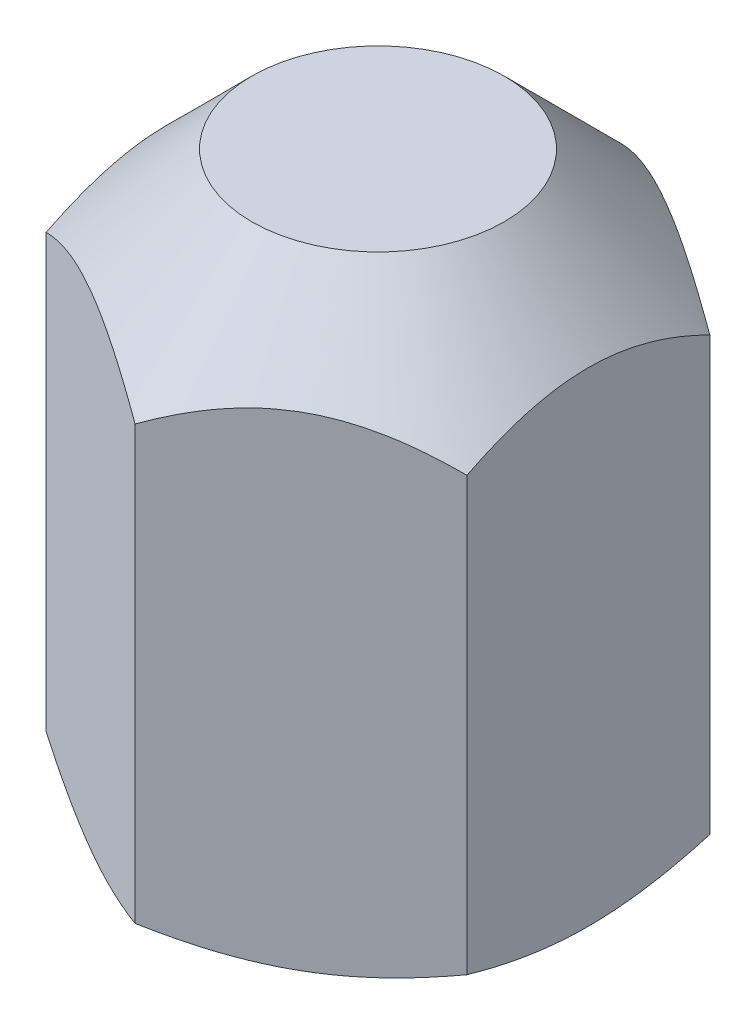
SolidWorks part; units mm, degrees
ref_plane "Přední rovina" through (0, 0, 0) normal (0, 0, 1) x (1, 0, 0)
ref_plane "Vrchní rovina" through (0, 0, 0) normal (0, 1, 0) x (1, 0, 0)
ref_plane "Pravá rovina" through (0, 0, 0) normal (1, 0, 0) x (0, 0, -1)
sketch "Skica1" plane through (0, 0, 0) normal (0, 1, 0) x (1, 0, 0)
  line L1 (5, -2.8868) -> (5, 2.8868)
  line L2 (5, 2.8868) -> (0, 5.7735)
  line L3 (0, 5.7735) -> (-5, 2.8868)
  line L4 (-5, 2.8868) -> (-5, -2.8868)
  line L5 (-5, -2.8868) -> (0, -5.7735)
  line L6 (0, -5.7735) -> (5, -2.8868)
  circle A0 centre (0, 0) radius 5 construction
  dimension "s" = 10
extrude "Vysunout1" add sketch "Skica1" along normal blind 13.5
sketch "Skica2" plane through (0, 0, 0) normal (1, 0, 0) x (0, 0, -1)
  line L0 (0, 13.5) -> (0, 0) construction
  line L1 (-2.8868, 13.5) -> (2.8868, 13.5) construction
  line L2 (-5.7735, 13.5) -> (-5.7735, 10.7265)
  line L3 (-5.7735, 13.5) -> (-5.7735, 0) construction
  line L4 (-5.7735, 10.7265) -> (-3, 13.5)
  line L5 (-3, 13.5) -> (-5.7735, 13.5)
  dimension "D1" = 45
  dimension "k" = 6
revolve "Odebrat otočením1" cut sketch "Skica2" angle 360 about L0
sketch "Skica3" plane through (0, 0, 0) normal (0, 0, 1) x (1, 0, 0)
  line L0 (5, 0) -> (28.3827, 0)
  line L1 (28.3827, 0) -> (28.3827, 13.5)
  line L2 (28.3827, 13.5) -> (5, 0)
  line L3 (3, 13.5) -> (-3, 13.5) construction
  line L4 (0, 0) -> (0, 13.5) construction
  dimension "D1" = 30
revolve "Odebrat otočením2" cut sketch "Skica3" angle 360 about L4
sketch "Skica4" plane through (0, 0, 0) normal (0, -1, 0) x (1, 0, 0)
  circle A0 centre (0, 0) radius 2.55
  dimension "D1" = 5.1
extrude "Odebrat vysunutím1" cut sketch "Skica4" against normal blind 12.5
cosmetic thread "Kosmetický závit1" parameters "b"=7.5, "M"=6
chamfer "Zkosit1" distance 0.6 angle 30 1 edges at (0, 0, -2.55)
equation "\"D1@Zkosit1\" = 0.1 * \"M@Kosmetický závit1\""
equation "\"D1@Skica4\" = 0.85 * \"M@Kosmetický závit1\""
